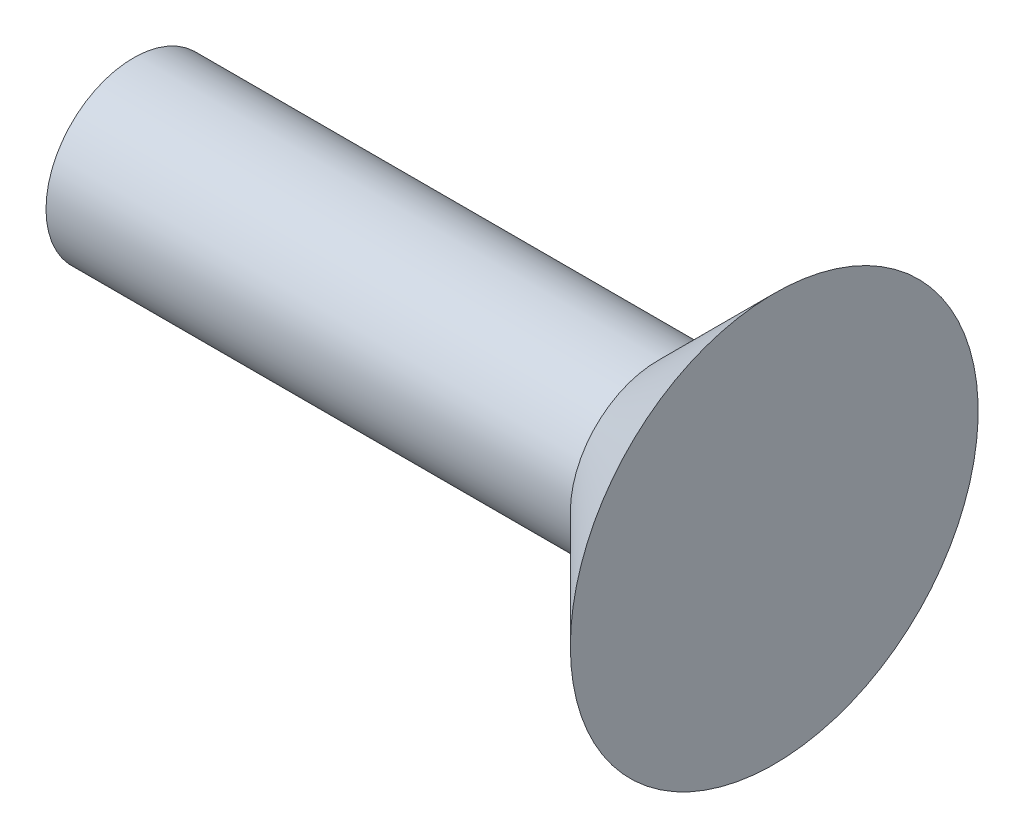
SolidWorks part; units mm, degrees
ref_plane "Front Plane" through (0, 0, 0) normal (0, 0, 1) x (1, 0, 0)
ref_plane "Top Plane" through (0, 0, 0) normal (0, 1, 0) x (1, 0, 0)
ref_plane "Right Plane" through (0, 0, 0) normal (1, 0, 0) x (0, 0, -1)
sketch "Sketch1" plane through (0, 0, 0) normal (0, 0, 1) x (1, 0, 0)
  line L0 (-84.0032, 19.2344) -> (-72.0032, 19.2344)
  line L1 (-70.0032, 17.7344) -> (-70.0032, 21.2344)
  line L2 (-84.0032, 19.2344) -> (-84.0032, 17.7344)
  line L3 (-72.0032, 19.2344) -> (-70.0032, 21.2344)
  line L4 (-84.0032, 17.7344) -> (-70.0032, 17.7344) construction
  line L5 (-70.0032, 17.7344) -> (-84.0032, 17.7344)
revolve "Revolve2" add sketch "Sketch1" angle 360 about L4
sketch "Sketch2" plane through (-84.0032, 0, 0) normal (-1, 0, 0) x (0, 0, 1)
  line L1 (-2.2284, 19.7227) -> (1.7866, 19.7227)
  line L2 (-2.2284, 19.7227) -> (-2.2284, 16.1111)
  line L3 (-2.2284, 16.1111) -> (1.7866, 16.1111)
  line L4 (1.7866, 19.7227) -> (1.7866, 16.1111)
extrude "Cut-Extrude1" cut sketch "Sketch2" against normal blind 3
